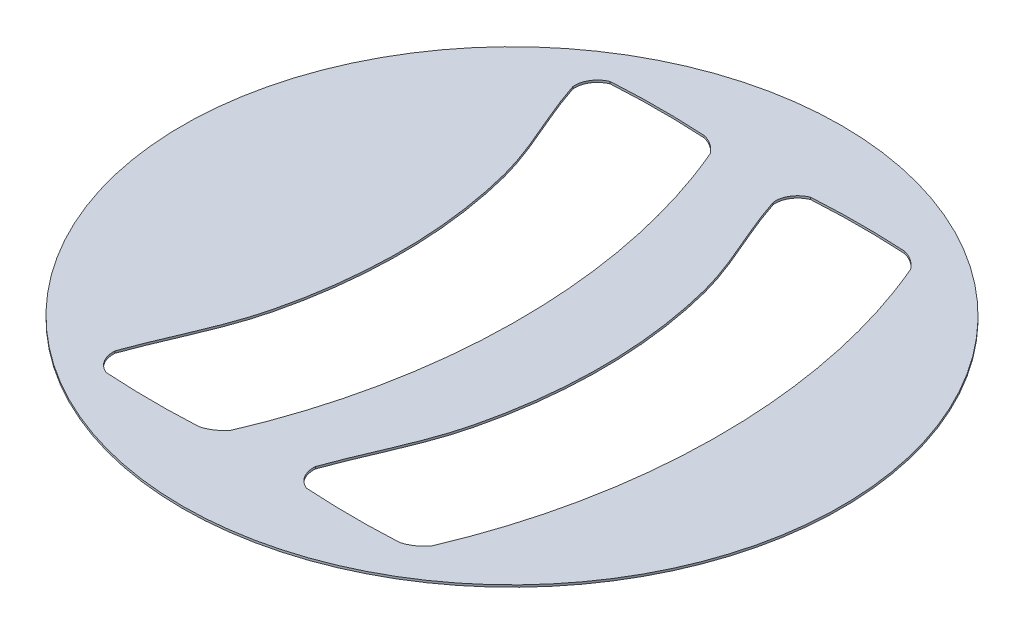
SolidWorks part; units mm, degrees
ref_plane "Front Plane" through (0, 0, 0) normal (0, 0, 1) x (1, 0, 0)
ref_plane "Top Plane" through (0, 0, 0) normal (0, 1, 0) x (1, 0, 0)
ref_plane "Right Plane" through (0, 0, 0) normal (1, 0, 0) x (0, 0, -1)
sketch "Sketch1" plane through (0, 0, 0) normal (0, 1, 0) x (1, 0, 0)
  arc A0 (53.0844, -95.7652) -> (17.6371, -95.5919) centre (36.806, 200.0206) cw
  arc A1 (17.6375, 95.5837) -> (53.1598, 95.6765) centre (36.1535, -193.3345) cw
  arc A2 (-58.3625, 95.5837) -> (-22.8402, 95.6765) centre (-39.8465, -193.3345) cw
  arc A3 (-22.9156, -95.7652) -> (-58.3629, -95.5919) centre (-39.194, 200.0206) cw
  circle A4 centre (0, 0) radius 125
  ellipse E0 centre (-78.6468, 0.1872) end of major axis (-78.1194, -193.9634) minor radius 157.2686 (60.3507, -90.8396) -> (60.3618, 90.7922) ccw
  ellipse E1 centre (-154.6468, 0.1872) end of major axis (-154.1194, -193.9634) minor radius 157.2686 (-15.6493, -90.8396) -> (-15.6382, 90.7922) ccw
  spline S0 degree 3 poles (60.3507, -90.8396) (58.5363, -93.2547) (56.0081, -95.0054) (53.0844, -95.7652) knots 0 0 0 0 1 1 1 1
  spline S1 degree 3 poles (17.6371, -95.5919) (14.0789, -94.1778) (11.9668, -90.6152) (12.2399, -86.796) knots 0 0 0 0 1 1 1 1
  spline S2 degree 3 poles (12.2399, -86.796) (17.2372, -72.6086) (24.4533, -59.2384) (31.8948, -30.0902) (33.7466, -15.0474) (33.7916, 15.0362) (31.8951, 30.0803) (24.4441, 59.2266) (16.8626, 72.4743) (12.2546, 86.7929) knots 0 0 0 0 0.25 0.25 0.5 0.5 0.75 0.75 1 1 1 1
  spline S3 degree 3 poles (12.2546, 86.7929) (11.8616, 90.6017) (14.1194, 94.0724) (17.6375, 95.5837) knots 0 0 0 0 1 1 1 1
  spline S4 degree 3 poles (53.1598, 95.6765) (56.0823, 94.9962) (58.5642, 93.1948) (60.3618, 90.7922) knots 0 0 0 0 1 1 1 1
  spline S5 degree 3 poles (-22.8402, 95.6765) (-19.9177, 94.9962) (-17.4358, 93.1948) (-15.6382, 90.7922) knots 0 0 0 0 1 1 1 1
  spline S6 degree 3 poles (-15.6493, -90.8396) (-17.4637, -93.2547) (-19.9919, -95.0054) (-22.9156, -95.7652) knots 0 0 0 0 1 1 1 1
  spline S7 degree 3 poles (-58.3629, -95.5919) (-61.9211, -94.1778) (-64.0332, -90.6152) (-63.7601, -86.796) knots 0 0 0 0 1 1 1 1
  spline S8 degree 3 poles (-63.7601, -86.796) (-58.7628, -72.6086) (-51.5467, -59.2384) (-44.1052, -30.0902) (-42.2534, -15.0474) (-42.2084, 15.0362) (-44.1049, 30.0803) (-51.5559, 59.2266) (-59.1374, 72.4743) (-63.7454, 86.7929) knots 0 0 0 0 0.25 0.25 0.5 0.5 0.75 0.75 1 1 1 1
  spline S9 degree 3 poles (-63.7454, 86.7929) (-64.1384, 90.6017) (-61.8806, 94.0724) (-58.3625, 95.5837) knots 0 0 0 0 1 1 1 1
extrude "Boss-Extrude1" add sketch "Sketch1" along normal blind 0.8 contours A4 A1 S4 E0 S0 A0 S1 S2 S3 S8 S9 A2 S5 E1 S6 A3 S7
